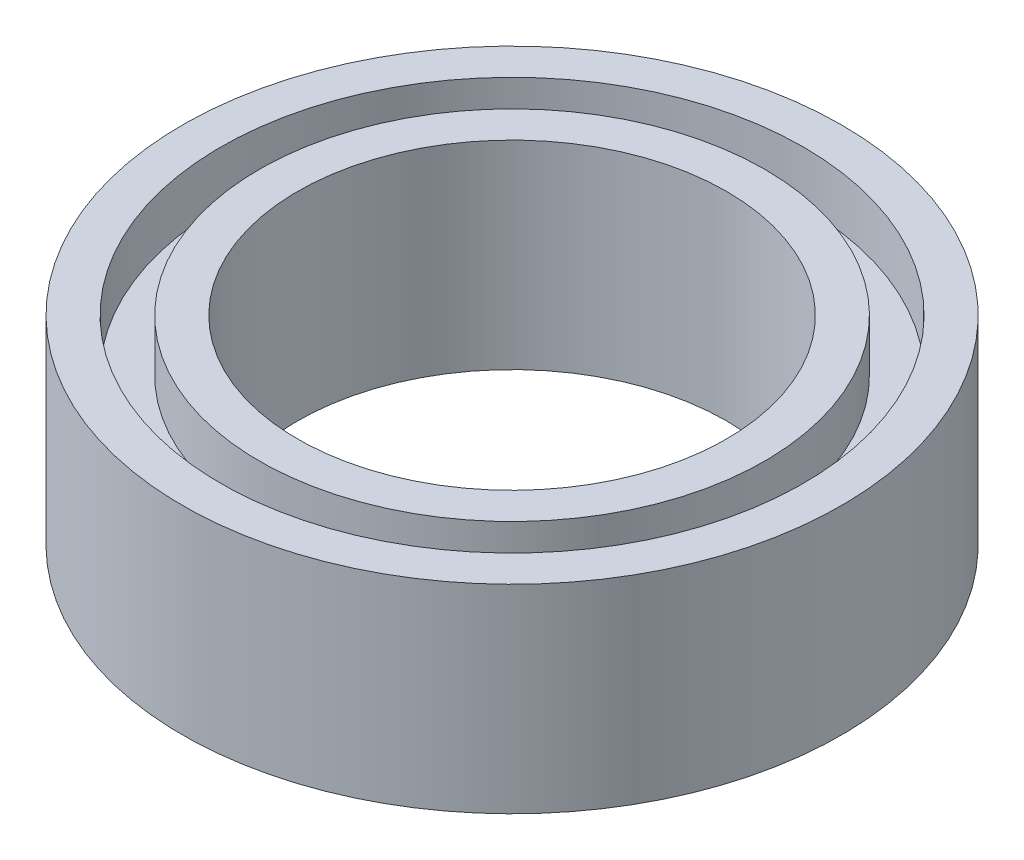
SolidWorks part; units mm, degrees
ref_plane "Front Plane" through (0, 0, 0) normal (0, 0, 1) x (1, 0, 0)
ref_plane "Top Plane" through (0, 0, 0) normal (0, 1, 0) x (1, 0, 0)
ref_plane "Right Plane" through (0, 0, 0) normal (1, 0, 0) x (0, 0, -1)
sketch "Sketch1" plane through (0, 0, 0) normal (0, 0, 1) x (1, 0, 0)
  line L0 (0, -13.1597) -> (0, 13.1597) construction
  line L1 (0, 0) -> (6.3, 0)
  line L2 (6.3, 0) -> (6.3, 6.0966)
  line L3 (6.3, 6.0966) -> (5.5694, 6.0966)
  line L4 (5.5694, 6.0966) -> (5.5694, 7.0966)
  line L5 (5.5694, 7.0966) -> (4.8306, 7.0966)
  line L6 (4.8306, 7.0966) -> (4.8306, 6.0966)
  line L7 (4.8306, 6.0966) -> (4.1, 6.0966)
  line L8 (4.1, 6.0966) -> (4.1, 9.8966)
  line L9 (4.1, 9.8966) -> (5.5694, 9.8966)
  line L10 (5.5694, 9.8966) -> (5.5694, 8.8966)
  line L11 (5.5694, 8.8966) -> (4.8306, 8.8966)
  line L12 (4.8306, 8.8966) -> (4.8306, 9.8966)
  line L13 (4.8306, 9.8966) -> (6.3, 9.8966)
  line L14 (6.3, 9.8966) -> (6.3, 6.0966)
  point P4 (0, 0)
  dimension "D1" = 1
  dimension "D2" = 1.4694
  dimension "D3" = 2.2
  dimension "D4" = 3.8
  dimension "D5" = 6.3
revolve "Revolve1" add sketch "Sketch1" angle 360 about L0
